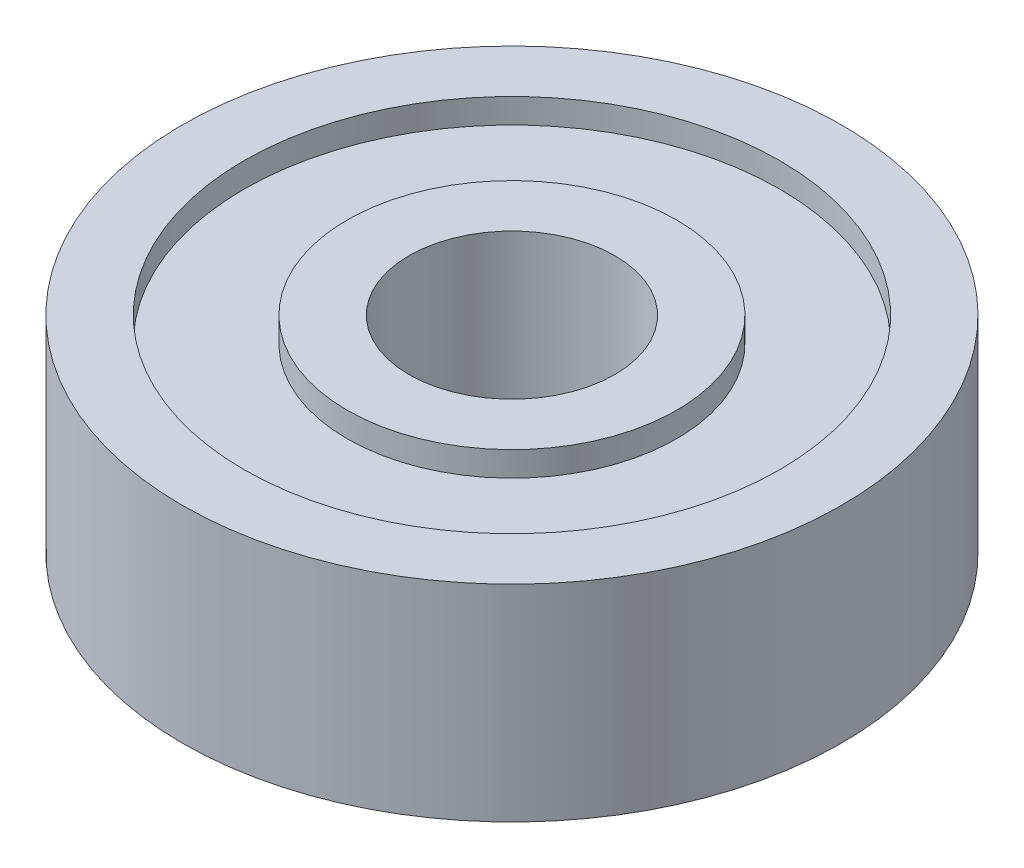
SolidWorks part; units mm, degrees
ref_plane "Front Plane" through (0, 0, 0) normal (0, 0, 1) x (1, 0, 0)
ref_plane "Top Plane" through (0, 0, 0) normal (0, 1, 0) x (1, 0, 0)
ref_plane "Right Plane" through (0, 0, 0) normal (1, 0, 0) x (0, 0, -1)
sketch "Sketch1" plane through (0, 0, 0) normal (0, 1, 0) x (1, 0, 0)
  circle A0 centre (0, 0) radius 2.5
  circle A1 centre (0, 0) radius 8
  dimension "D1" = 16
  dimension "D2" = 5
extrude "Boss-Extrude1" add sketch "Sketch1" along normal blind 5
sketch "Sketch2" plane through (0, 5, 0) normal (0, 1, 0) x (1, 0, 0)
  circle A0 centre (0, 0) radius 4
  circle A1 centre (0, 0) radius 6.5
  dimension "D1" = 13
  dimension "D2" = 8
extrude "Cut-Extrude1" cut sketch "Sketch2" against normal blind 0.6
sketch "Sketch3" plane through (0, 0, 0) normal (0, -1, 0) x (1, 0, 0)
  circle A0 centre (0, 0) radius 4
  circle A1 centre (0, 0) radius 6.5
  dimension "D1" = 8
  dimension "D2" = 13
extrude "Cut-Extrude2" cut sketch "Sketch3" against normal blind 0.6
